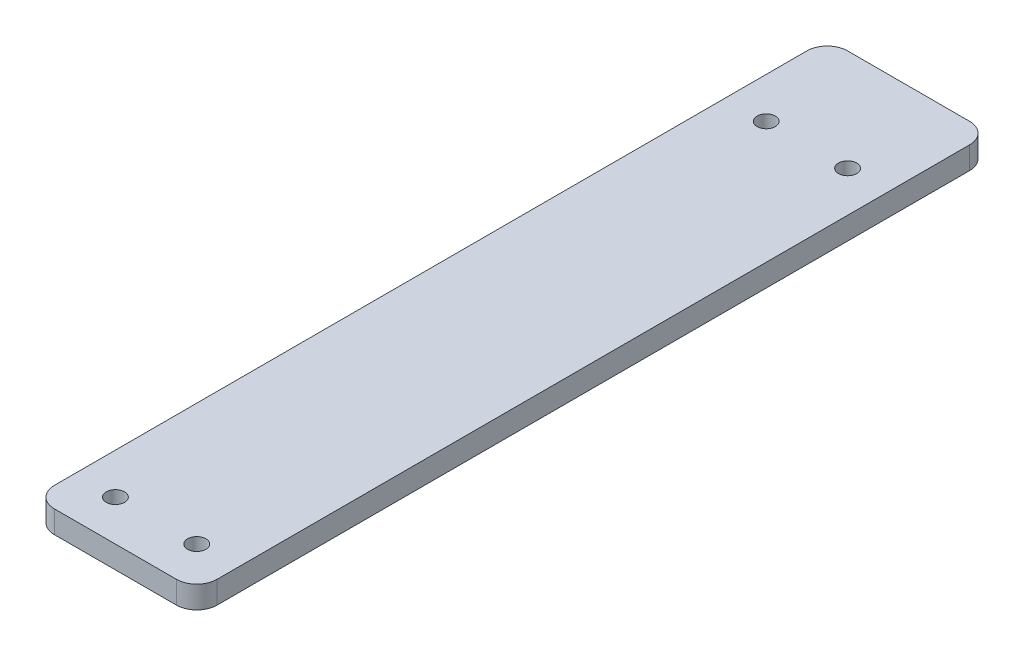
SolidWorks part; units mm, degrees
ref_plane "Alzado" through (0, 0, 0) normal (0, 0, 1) x (1, 0, 0)
ref_plane "Planta" through (0, 0, 0) normal (0, 1, 0) x (1, 0, 0)
ref_plane "Vista lateral" through (0, 0, 0) normal (1, 0, 0) x (0, 0, -1)
sketch "Croquis1" plane through (0, 0, 0) normal (0, 1, 0) x (1, 0, 0)
  line L0 (0, -5) -> (0, -190)
  line L1 (-5, -195) -> (-35, -195)
  line L2 (-40, -190) -> (-40, -5)
  line L3 (-35, 0) -> (-5, 0)
  line L4 (-40, 0) -> (-30, 0) construction
  line L5 (-35, -5) -> (-5, -5) construction
  line L6 (-5, -5) -> (-5, -190) construction
  line L7 (-5, -190) -> (-35, -190) construction
  line L8 (-35, -190) -> (-35, -5) construction
  circle A0 centre (-30, -25) radius 2.25
  circle A1 centre (-10, -25) radius 2.25
  circle A2 centre (-30, -185) radius 2.25
  circle A3 centre (-10, -185) radius 2.25
  arc A4 (-35, 0) -> (-40, -5) centre (-35, -5) ccw
  arc A5 (0, -5) -> (-5, 0) centre (-5, -5) ccw
  arc A8 (-40, -190) -> (-35, -195) centre (-35, -190) ccw
  arc A9 (-5, -195) -> (0, -190) centre (-5, -190) ccw
  dimension "D3" = 4.5
  dimension "D4" = 4.5
  dimension "D6" = 25
  dimension "D13" = 4.5
  dimension "D14" = 4.5
  dimension "D15" = 5
  dimension "D16" = 5
  dimension "D5" = 25
  dimension "D7" = 20
  dimension "D8" = 10
  dimension "D9" = 10
  dimension "D10" = 20
  dimension "D11" = 10
  dimension "D12" = 10
  dimension "D17" = 5
  dimension "D18" = 5
extrude "Saliente-Extruir1" add sketch "Croquis1" along normal blind 5.5
